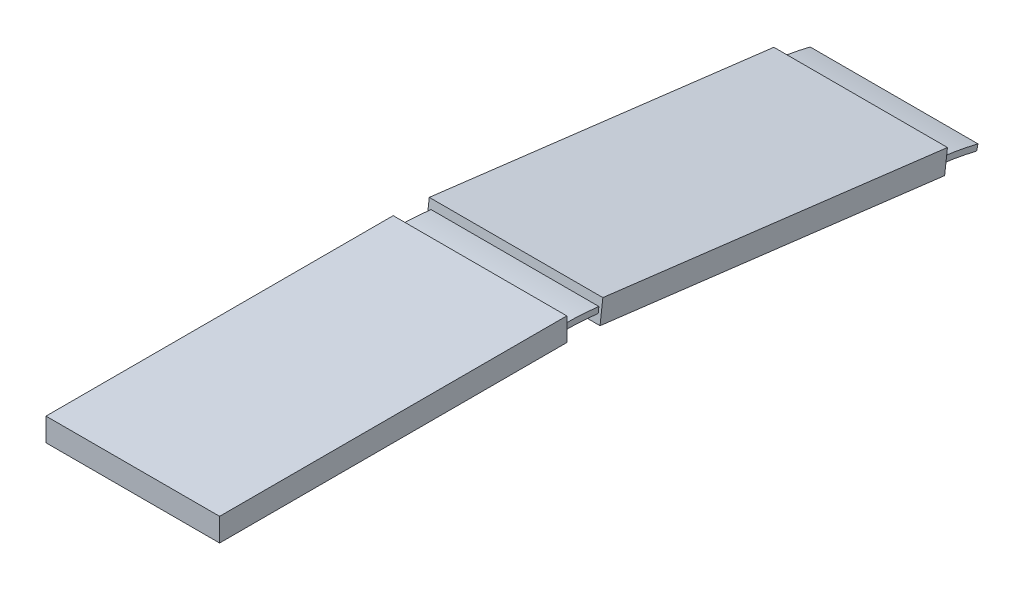
SolidWorks part; units mm, degrees
material "Thornel Mat VMA"
ref_plane "Front Plane" through (0, 0, 0) normal (0, 0, 1) x (1, 0, 0)
ref_plane "Top Plane" through (0, 0, 0) normal (0, 1, 0) x (1, 0, 0)
ref_plane "Right Plane" through (0, 0, 0) normal (1, 0, 0) x (0, 0, -1)
sketch "Sketch1" plane through (0, 0, 0) normal (0, 1, 0) x (1, 0, 0)
  line L1 (0.75, -1.5) -> (-0.75, -1.5)
  line L2 (0.75, -1.5) -> (0.75, 1.5)
  line L3 (0.75, 1.5) -> (-0.75, 1.5)
  line L4 (-0.75, -1.5) -> (-0.75, 1.5)
  line L5 (0, 1.5) -> (0, -1.5) construction
  line L6 (0.75, 0) -> (-0.75, 0) construction
  point P0 (0, 0)
  dimension "D1" = 3
  dimension "D2" = 1.5
extrude "Boss-Extrude1" add sketch "Sketch1" along normal mid plane 0.2
sketch "Sketch3" plane through (0, 0, 0) normal (1, 0, 0) x (0, 0, -1)
  line L0 (1.5, 0.025) -> (1.5, -0.025)
  line L1 (1.5, 0.1) -> (1.5, -0.1) construction
  line L2 (1.8025, 0.0065) -> (1.7964, -0.0431)
  line L3 (1.5, 0.025) -> (1.6056, 0.025) construction
  line L4 (1.5, 0) -> (1.6503, 0) construction
  line L5 (1.7964, -0.0431) -> (1.2433, -4.5474) construction
  line L6 (1.7994, -0.0183) -> (1.6503, 0) construction
  arc A0 (1.5, -0.025) -> (1.7964, -0.0431) centre (1.5, -2.4571) cw
  arc A1 (1.5, 0.025) -> (1.8025, 0.0065) centre (1.5, -2.4571) cw
  arc A2 (1.5, 0) -> (1.7994, -0.0183) centre (1.5, -2.4571) cw construction
  point P12 (1.6515, 0.0204)
  point P14 (1.6485, -0.0295)
  dimension "D1" = 0.05
  dimension "D2" = 0.05
  dimension "D3" = 0.3
  dimension "D4" = 7
  dimension "D5" = 0.05
extrude "Boss-Extrude3" add sketch "Sketch3" along normal mid plane 1.45
sketch "Sketch4" plane through (0, 0, 0) normal (1, 0, 0) x (0, 0, -1)
  line L0 (1.7964, -0.0431) -> (1.8025, 0.0065) construction
  line L1 (1.7873, -0.1176) -> (1.8116, 0.0809)
  line L2 (1.8116, 0.0809) -> (4.7893, -0.2847)
  line L3 (4.7893, -0.2847) -> (4.7649, -0.4832)
  line L4 (4.7649, -0.4832) -> (1.7873, -0.1176)
  point P7 (1.7994, -0.0183)
  point P8 (1.7994, -0.0183)
  dimension "D1" = 0.2
  dimension "D2" = 3
extrude "Boss-Extrude4" add sketch "Sketch4" along normal mid plane 1.5
sketch "Sketch6" plane through (0, 0, 0) normal (1, 0, 0) x (0, 0, -1)
  line L0 (4.7801, -0.3591) -> (4.774, -0.4087)
  line L2 (5.0781, -0.4143) -> (5.066, -0.4629)
  line L3 (4.7801, -0.3591) -> (1.5858, 0.0331) construction
  line L4 (4.7771, -0.3839) -> (4.9262, -0.4022) construction
  line L5 (5.066, -0.4629) -> (4.312, -3.4871) construction
  line L6 (5.0721, -0.4386) -> (4.9262, -0.4022) construction
  line L7 (4.7649, -0.4832) -> (4.7893, -0.2847) construction
  arc A0 (4.774, -0.4087) -> (5.066, -0.4629) centre (4.4776, -2.8227) cw
  arc A1 (4.7801, -0.3591) -> (5.0781, -0.4143) centre (4.4776, -2.8227) cw
  arc A2 (4.7771, -0.3839) -> (5.0721, -0.4386) centre (4.4776, -2.8227) cw construction
  point P12 (4.93, -0.3822)
  point P14 (4.9208, -0.4313)
  point P24 (4.7771, -0.3839)
  dimension "D1" = 0.05
  dimension "D2" = 0.05
  dimension "D3" = 0.3
  dimension "D4" = 7
  dimension "D5" = 0.05
extrude "Boss-Extrude5" add sketch "Sketch6" along normal mid plane 1.45
sketch "Sketch7" plane through (0, 0, 1.5) normal (0, 0, 1) x (1, 0, 0)
  line L0 (-0.75, 0) -> (0.75, 0) construction
  line L1 (-0.75, 0.1) -> (-0.75, -0.1) construction
  line L2 (0.75, 0.1) -> (0.75, -0.1) construction
sketch "Sketch8" plane through (0, -1.2163, -4.8782) normal (0, -0.2419, -0.9703) x (-1, 0, 0)
  line L0 (-0.725, 0.8015) -> (0.725, 0.8015) construction
  line L1 (-0.725, 0.7765) -> (-0.725, 0.8265) construction
  line L2 (0.725, 0.7765) -> (0.725, 0.8265) construction
equation "\"cf_length\"= 3mm"
equation "\"cf_width\" = 1.5mm"
equation "\"cf_thickness\"= .2mm"
equation "\"kap_length\"= .3mm"
equation "\"kap_depth\"= .05mm"
equation "\"kap_curvature\" = 7deg'total angle of curvature for kapton hinge"
equation "\"D1@Sketch1\"=\"cf_length\""
equation "\"D2@Sketch1\"=\"cf_width\""
equation "\"D1@Boss-Extrude1\"=\"cf_thickness\""
equation "\"D1@Sketch3\"=\"kap_depth\""
equation "\"D2@Sketch3\"=\"kap_depth\""
equation "\"D3@Sketch3\"=\"kap_length\""
equation "\"D4@Sketch3\"=\"kap_curvature\""
equation "\"D5@Sketch3\"=\"kap_depth\""
equation "\"D1@Boss-Extrude3\"=\"cf_width\"-\"kap_depth\""
equation "\"D1@Sketch4\"=\"cf_thickness\""
equation "\"D2@Sketch4\"=\"cf_length\""
equation "\"D1@Boss-Extrude4\"=\"cf_width\""
equation "\"D4@Sketch6\"=\"kap_curvature\""
equation "\"D5@Sketch6\"=\"kap_depth\""
equation "\"D2@Sketch6\"=\"kap_depth\""
equation "\"D3@Sketch6\"=\"kap_length\""
equation "\"D1@Boss-Extrude5\"=\"cf_width\"-\"kap_depth\""
